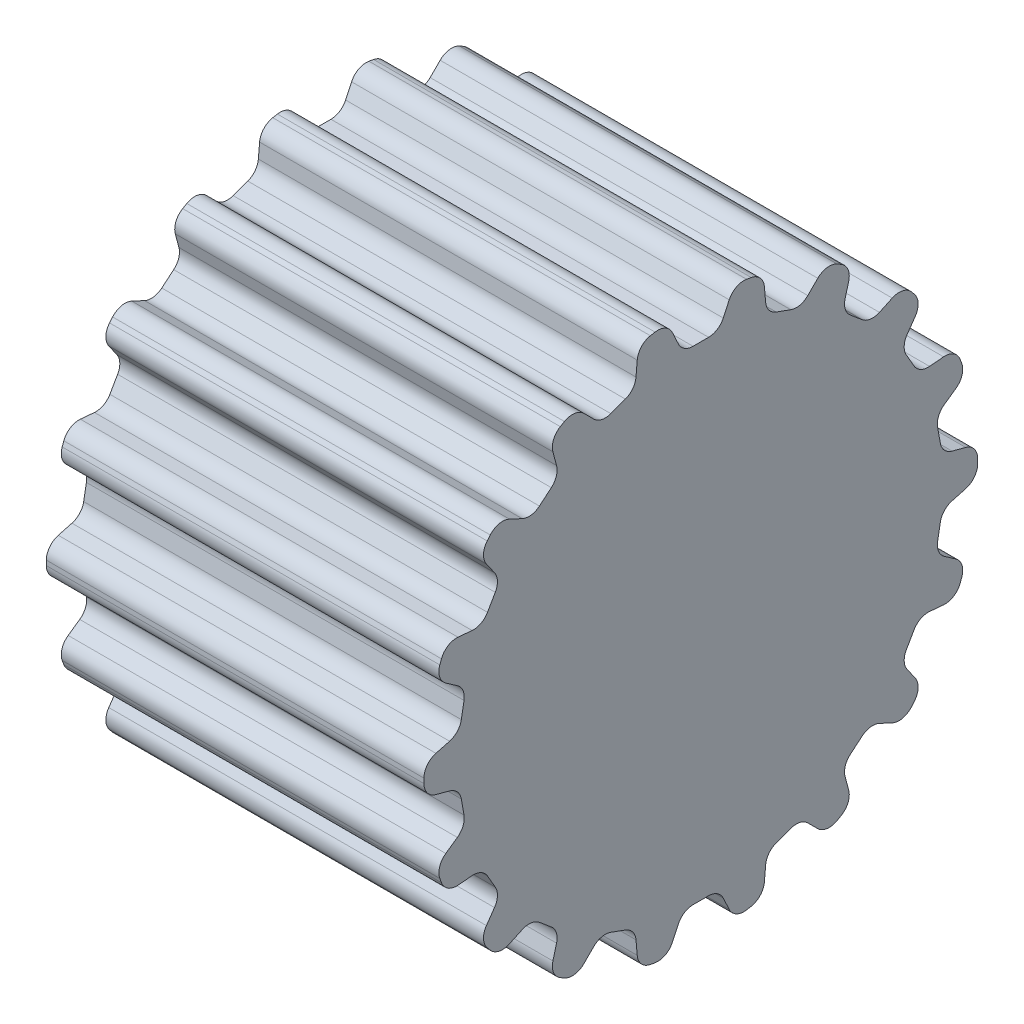
SolidWorks part; units mm, degrees
ref_plane "Front Plane" through (0, 0, 0) normal (0, 0, 1) x (1, 0, 0)
ref_plane "Top Plane" through (0, 0, 0) normal (0, 1, 0) x (1, 0, 0)
ref_plane "Right Plane" through (0, 0, 0) normal (1, 0, 0) x (0, 0, -1)
sketch "Sketch1" plane through (0, 0, 0) normal (1, 0, 0) x (0, 0, -1)
  line L0 (-0.5264, 4.8931) -> (-0.4158, 4.6559)
  line L1 (-0.1439, 4.4827) -> (0.1439, 4.4827)
  line L2 (0.4158, 4.6559) -> (0.5264, 4.8931)
  line L3 (-0.8913, 5.0547) -> (0, 0)
  line L4 (0, 0) -> (0.8913, 5.0547)
  arc A0 (-0.8913, 5.0547) -> (-0.8478, 5.0622) centre (0, 0) cw
  arc A1 (0.8478, 5.0622) -> (0.8913, 5.0547) centre (0, 0) cw
  arc A2 (-0.6205, 5.0951) -> (0.6205, 5.0951) centre (0, 0) cw construction
  arc A3 (0.5264, 4.8931) -> (0.8478, 5.0622) centre (0.7983, 4.7663) cw
  arc A4 (0.1439, 4.4827) -> (0.4158, 4.6559) centre (0.1439, 4.7827) ccw
  arc A5 (-0.4158, 4.6559) -> (-0.1439, 4.4827) centre (-0.1439, 4.7827) ccw
  arc A6 (-0.8478, 5.0622) -> (-0.5264, 4.8931) centre (-0.7983, 4.7663) cw
  arc A7 (-1.0128, 5.7441) -> (1.0128, 5.7441) centre (0, 0) cw construction
  point P1 (0, 5.1327)
  point P3 (0, 4.4827)
  point P13 (-1.6914, 6.5748)
  point P21 (0.335, 4.4827)
  point P24 (-0.335, 4.4827)
  point P28 (0, 0)
  dimension "D6" = 0.3
  dimension "D1" = 115
  dimension "D2" = 115
  dimension "D3" = 0.67
  dimension "D5" = 0.65
  dimension "D4" = 20
  dimension "D8" = 0.7
  dimension "D7" = 2.036
extrude "Boss-Extrude1" add sketch "Sketch1" along normal blind 7
pattern_circular "CirPattern1" count 18 over 360 about axis through (0, 0, 0) along (1, 0, 0) of "Boss-Extrude1"
equation "\"teeth\"= 18"
equation "\"angle\"= 360 / \"teeth\""
equation "\"D4@Sketch1\"=\"angle\""
equation "\"D1@CirPattern1\"=\"teeth\""
